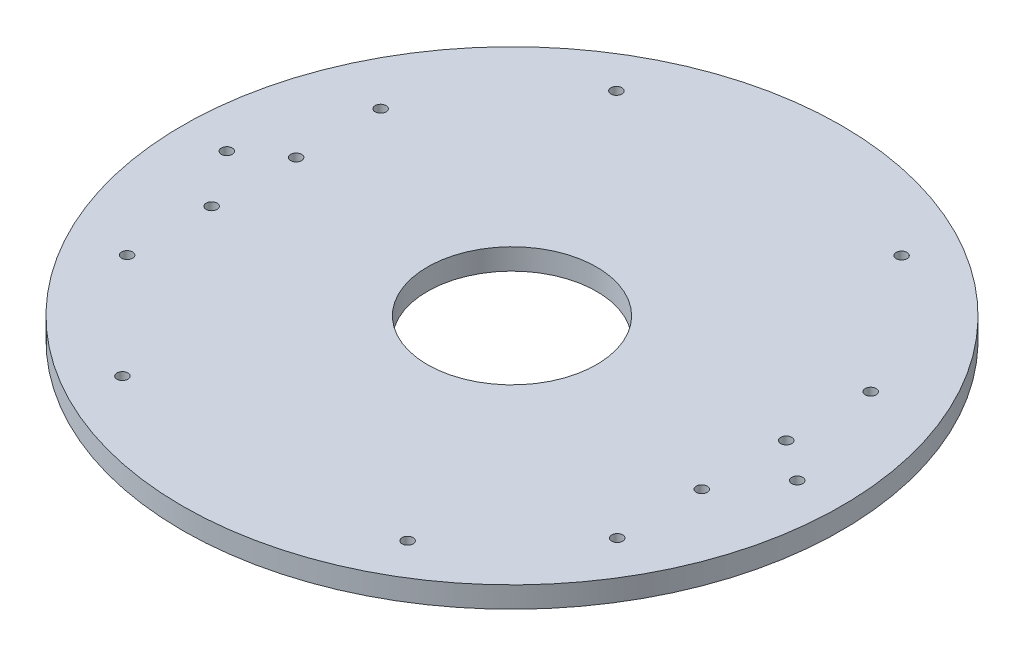
SolidWorks part; units mm, degrees
ref_plane "Спереди" through (0, 0, 0) normal (0, 0, 1) x (1, 0, 0)
ref_plane "Сверху" through (0, 0, 0) normal (0, 1, 0) x (1, 0, 0)
ref_plane "Справа" through (0, 0, 0) normal (1, 0, 0) x (0, 0, -1)
sketch "Эскиз1" plane through (0, 0, 0) normal (0, 1, 0) x (1, 0, 0)
  circle A0 centre (0, 0) radius 156
  dimension "D1" = 312
extrude "Бобышка-Вытянуть1" add sketch "Эскиз1" along normal blind 10
sketch "Эскиз2" plane through (0, 10, 0) normal (0, 1, 0) x (1, 0, 0)
  line L0 (-116, 0) -> (116, 0) construction
  line L1 (116, 0) -> (116, 13.8) construction
  line L2 (0, 0) -> (0, 21.6567) construction
  line L3 (-116, 0) -> (-116, 13.8) construction
  circle A0 centre (116, 13.8) radius 2.6
  circle A1 centre (116, 53.8) radius 2.6
  circle A2 centre (116, 13.8) radius 2.6
  circle A3 centre (116, -26.2) radius 2.6
  circle A4 centre (116, -26.2) radius 2.6
  circle A5 centre (116, -66.2) radius 2.6
  circle A6 centre (-116, -66.2) radius 2.6
  circle A7 centre (-116, -26.2) radius 2.6
  circle A8 centre (-116, -26.2) radius 2.6
  circle A9 centre (-116, 13.8) radius 2.6
  circle A10 centre (-116, 53.8) radius 2.6
  circle A11 centre (-116, 13.8) radius 2.6
  point P19 (0, 0)
  dimension "D3" = 5.2
  dimension "D1" = 116
  dimension "D2" = 13.8
  dimension "D4" = 2
  dimension "D5" = 3
extrude "Вырез-Вытянуть1" cut sketch "Эскиз2" against normal through all contours A3 | A5 | A0 | A1 | A10 | A9 | A7 | A6
sketch "Эскиз3" plane through (0, 10, 0) normal (0, 1, 0) x (1, 0, 0)
  circle A0 centre (0, 0) radius 40.05
  dimension "D1" = 80.1
extrude "Вырез-Вытянуть2" cut sketch "Эскиз3" against normal blind 10
sketch "Эскиз4" plane through (0, 10, 0) normal (0, 1, 0) x (1, 0, 0)
  circle A2 centre (0, 0) radius 135 construction
  circle A3 centre (-135, 0) radius 2.6
  point P1 (0, 0)
  dimension "D1" = 270
  dimension "D2" = 5.2
extrude "Вырез-Вытянуть4" cut sketch "Эскиз4" against normal through all contours A3
pattern_circular "Круговой массив1" count 6 over 360 about axis through (0, 0, 0) along (0, 1, 0) of "Вырез-Вытянуть4"
